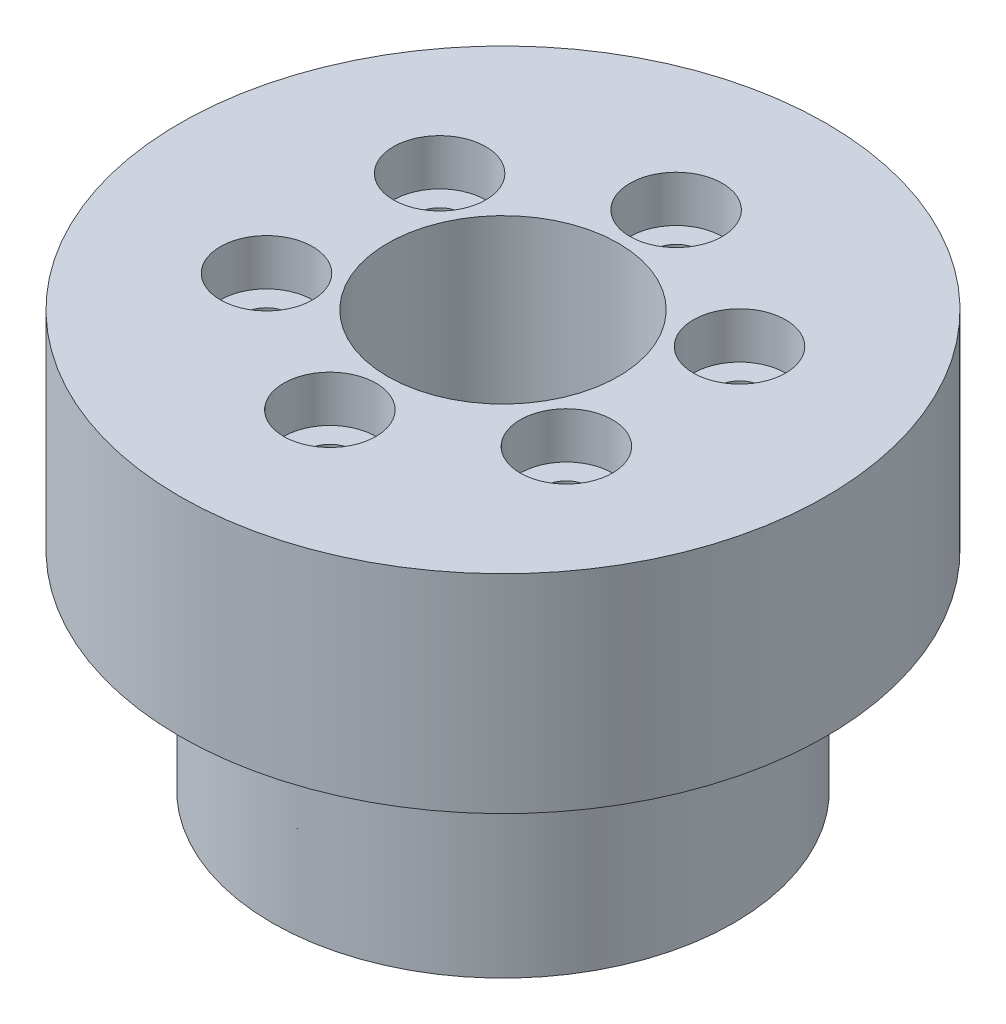
SolidWorks part; units mm, degrees
material "1060 Alloy"
ref_plane "Front" through (0, 0, 0) normal (0, 0, 1) x (1, 0, 0)
ref_plane "Top" through (0, 0, 0) normal (0, 1, 0) x (1, 0, 0)
ref_plane "Right" through (0, 0, 0) normal (1, 0, 0) x (0, 0, -1)
sketch "Sketch1" plane through (0, 0, 0) normal (0, 0, 1) x (1, 0, 0)
  line L0 (0, 0) -> (20, 0)
  line L1 (20, 0) -> (20, 18)
  line L2 (20, 18) -> (28, 18)
  line L3 (28, 18) -> (28, 36)
  line L6 (28, 36) -> (0, 36)
  line L7 (0, 36) -> (0, 0)
  point P3 (20, 38)
  point P8 (20, 38)
  point P11 (24.6535, 38)
  dimension "D1" = 18
  dimension "D2" = 18
  dimension "D3" = 8
  dimension "D4" = 20
revolve "Revolve1" add sketch "Sketch1" angle 360 about L7
sketch "Sketch2" plane through (0, 36, 0) normal (0, 1, 0) x (1, 0, 0)
  line L0 (0, 0) -> (0, 15) construction
  circle A0 centre (0, 0) radius 15 construction
  circle A1 centre (0, 15) radius 2
  circle A2 centre (0, 0) radius 15 construction
  circle A3 centre (12.9904, 7.5) radius 2
  circle A4 centre (0, 0) radius 15 construction
  circle A5 centre (12.9904, -7.5) radius 2
  circle A6 centre (0, 0) radius 15 construction
  circle A7 centre (0, -15) radius 2
  circle A8 centre (0, 0) radius 15 construction
  circle A9 centre (-12.9904, -7.5) radius 2
  circle A10 centre (0, 0) radius 15 construction
  circle A11 centre (-12.9904, 7.5) radius 2
  point P23 (0, 0)
  dimension "D1" = 30
  dimension "D2" = 4
extrude "Cut-Extrude1" cut sketch "Sketch2" against normal through all
sketch "Sketch3" plane through (0, 36, 0) normal (0, 1, 0) x (1, 0, 0)
  line L0 (0, 13) -> (0, 10) construction
  circle A0 centre (0, 0) radius 10
  circle A1 centre (0, 15) radius 2 construction
  dimension "D1" = 3
extrude "Cut-Extrude2" cut sketch "Sketch3" against normal through all
sketch "Sketch4" plane through (0, 36, 0) normal (0, 1, 0) x (1, 0, 0)
  circle A0 centre (0, 15) radius 4
  circle A1 centre (12.9904, 7.5) radius 4
  circle A2 centre (12.9904, -7.5) radius 4
  circle A3 centre (0, -15) radius 4
  circle A4 centre (-12.9904, -7.5) radius 4
  circle A5 centre (-12.9904, 7.5) radius 4
  point P15 (0, 0)
extrude "Cut-Extrude3" cut sketch "Sketch4" against normal blind 4
equation "\"D1@base\" = \"motor mount plate thickness\""
equation "\"coupler motor shaft hole ID\"= 8mm"
equation "\"coupler OD\"= 17mm"
equation "\"coupler length\"= 25mm"
equation "\"square plate bolt pattern diameter\"= 3.5in"
equation "\"motor mount m4 screw hole diameter\"= 4mm"
equation "\"motor mount m4 head diameter\"= 7.25mm"
equation "\"motor mount m4 head depth\"= 4mm"
equation "\"motor mount plate thickness\"= 8mm + \"motor mount m4 head depth\""
equation "\"motor shaft pride\"= 32mm"
equation "\"motor mount m4 pattern diamater\" = 30mm"
equation "\"motor OD\" = 64mm"
equation "\"square plate bolt bore\" = \"m8 clearance\""
equation "\"square plate bolt head diameter\" = 13.5mm"
equation "\"motor to bearing plate distance\" = \"motor shaft pride\" + 2mm +\"coupler length\"/2"
equation "\"motor mount center bore\"= \"coupler OD\"+ 4mm"
equation "\"motor mount post radius\"= ( 3 * \"square plate bolt bore\" ) / 2"
equation "\"motor shaft diameter\"= 8mm"
equation "\"D1\" = 20mm"
equation "\"z\" = 8\t\t\t\t'number of blades"
equation "\"de\" = 0.43in\t\t\t'entrance eye diameter"
equation "\"de_length\" = 4mm\t\t'entrance eye consistent length"
equation "\"d_exit\" = 0.18in \t\t'throat aka d1"
equation "\"d2\" = 2.1in \t\t\t'outer diameter of the impeller"
equation "\"b2\" = .2in\t\t\t'tip height from disc surface at d2; slightly higher than d_exit"
equation "\"theta\" = 12\t\t\t'angle of blades from inner to outer "
equation "\"ae\" = 3.14*(\"de\"^2)/4\t\t'entrance eye area'"
equation "\"ce\" = 3.14*\"de\"\t\t'entrance eye circumference"
equation "\"av_ratio\" = .325\t\t'ratio of av/ae at N_s of 470, range is .275 to .375, .325 ideal. High ratio means bigger area means smaller blades"
equation "\"av\" = \"ae\"*\"av_ratio\"\t\t'area between just two blades"
equation "\"min blade thickness\" = .15in"
equation "\"diffuser cartridge OD\" =.75in"
equation "\"diffuser flange bolt pattern diameter\" = 1.4in"
equation "\"bearing OD\" = 30mm"
equation "\"bearing ID\"= 10mm"
equation "\"bearing depth\"= 9mm"
equation "\"bearing outer race thickness\"= 1mm"
equation "\"bearing inner race thickness\"= 1mm"
equation "\"bearing bore\" = \"bearing depth\" + 1mm"
equation "\"lower seal OD\" = .917in\t\t'this is https://www.mcmaster.com/#9281k121/=174001b"
equation "\"lower seal ID\"= .375in"
equation "\"lower seal depth\" = .625in + .218in"
equation "\"lower seal bore\" = \"lower seal depth\" + 1mm"
equation "\"upper seal OD\" = 1.125in\t'this is https://www.mcmaster.com/#5154t33/=173zuau, needs to be visually inspected before machining!"
equation "\"upper seal ID\"= 0.625in"
equation "\"upper seal depth\"= .25in\t'aka height; these values need to be confirmed by inspection!! We may want to compress the height."
equation "\"upper seal bore\" = \"upper seal depth\" + 1mm"
equation "\"big o-ring thickness\" = .139in"
equation "\"big o-ring OD\" = 2.734in"
equation "\"big o-ring ID\" = 3.012in"
equation "\"big o-ring groove depth\" = \"big o-ring thickness\"*4/5"
equation "\"impeller upper clearance\"= .5mm"
equation "\"impeller horizontal clearance\"= (\"d2\"*1.15 - \"d2\")/2 \t\t'clearance based on D2-D3 ratio for circular volute, ranges 1.15 to 1.2"
equation "\"impeller bottom clearance\"= .5mm"
equation "\"impeller base thickness\"= 2mm"
equation "\"impeller dowel diameter\" = 2mm"
equation "\"impeller bolt head depth\" = 4mm"
equation "\"impeller bolt stop depth\" = 3mm"
equation "\"impeller shaft bore depth\" = 12mm"
equation "\"impeller shaft bore\" = 8mm"
equation "\"impeller boss depth\" = \"impeller shaft bore depth\"+\"impeller bolt stop depth\"+\"impeller bolt head depth\"-\"impeller base thickness\""
equation "\"impeller boss diameter\" = \"upper seal ID\""
equation "\"impeller dowel length\" = 2mm*2 + \"impeller shaft bore\""
equation "\"square plate bolt head depth\" = 8mm"
equation "\"bearing plate stop ID\" = \"bearing OD\" - 4mm"
equation "\"bearing plate stop depth\" = 3mm"
equation "\"lower seal plate lip depth\" = 2mm"
equation "\"lower seal plate lip ID\" = \"lower seal OD\" - 3mm"
equation "\"lower seal plate thickness\" = \"lower seal plate lip depth\" + \"lower seal bore\""
equation "\"shaft coupler section diameter\" = 8mm"
equation "\"shaft coupler section length\" = \"motor to bearing plate distance\" - \"motor shaft pride\" - 2mm"
equation "\"shaft bearing section diameter\" = \"bearing ID\""
equation "\"shaft bearing section length\" = \"bearing plate stop depth\" + \"bearing depth\""
equation "\"shaft bearing stop diameter\" = \"bearing ID\" + 4mm"
equation "\"shaft bearing stop length\" = 3mm"
equation "\"shaft lower seal section diameter\" = \"lower seal ID\""
equation "\"shaft lower seal section length\" = \"lower seal plate thickness\" + 1mm"
equation "\"shaft impeller section diameter\" = \"impeller shaft bore\""
equation "\"upper seal plate lip ID\" = \"upper seal OD\" - 3mm"
equation "\"upper seal plate riser\" = 6.59mm \t\t'this number needs to be read from the housing file"
equation "\"upper seal plate pressure hole diameter\" = .125in\t'this is 1/8 drill "
equation "\"upper seal plate pressure tap diameter\" = .328125in \t'this is 21/64 drill for a 1/8 ANPT tap"
equation "\"upper seal plate pressure tap grip\" = 5mm\t\t'this is the area around the tap so it doesn't crack"
equation "\"upper seal plate pressure tap depth\" = 12mm"
equation "\"impeller cavity diameter\"= 2 * \"impeller horizontal clearance\" + \"d2\" \t\t\t\t\t\t\t\t\t'called D3 analytically"
equation "\"impeller cavity outer height\"= \"impeller bottom clearance\" + \"impeller upper clearance\" + \"impeller base thickness\" + \"b2\" \t\t'this is height at impeller diameter d2, not at d3"
equation "\"impeller housing diameter\" = 4.5in"
equation "\"impeller housing bolt count\" = 8"
equation "\"impeller housing bolt pattern diameter\" = 3.5in"
equation "\"impeller housing threaded inlet diameter\" = 0.71875in \t'this is the 23/32 drill size for 1/2 NPT fitting https://www.mcmaster.com/#50715k269/=176pljy"
equation "\"impeller housing threaded inlet depth\"= .6in"
equation "\"impeller housing exit threaded diameter\"= 0.515625in \t\t'this is the 33/64 drill size for 9/16-18 fitting, expecting swagelok SS-8FK0-1-6STH fitting"
equation "\"impeller housing exit threaded depth\"= 10mm"
equation "\"impeller housing diffuser conical angle\"=10"
equation "\"impeller housing diffuser tangent angle\"=5"
equation "\"impeller housing diffuser final diameter\" = .38in\t\t'aka d2'"
equation "\"impeller housing outlet grip\" = 5mm"
equation "\"end mill size\" = 0.375in\t'for 3/8 endmill"
equation "\"m4 clearance\" = 0.171875in \t'this is 11/64 bit for 4.36mm"
equation "\"m4 tap\" = 0.125in\t\t'this is 1/8 bit for 3.17mm"
equation "\"m4 head bore diameter\" = 7.5mm"
equation "\"m4 head bore depth\" = 5mm\t'actual is ~4mm"
equation "\"m6 clearance\" = 0.234375in\t'this is 15/64 bit = 5.95mm, could use 6mm bit, B bit for 6.04mm or 1/4 bit for 6.35mm"
equation "\"m6 tap\" = 5mm\t\t\t'5mm is appropriate, could use 13/64 or #5,6,7"
equation "\"m6 head bore diameter\" = 11mm\t\t"
equation "\"m6 head bore depth\" = 7mm\t'actual is 6mm"
equation "\"m8 clearance\" = 0.3125in\t'this is 5/16in for 7.93mm, could use 8mm, O,P, or 21/64"
equation "\"m8 tap\" = 0.265625in\t\t'this is 17/64 for 6.746875mm"
equation "\"m8 head bore diameter\" = 14mm"
equation "\"m8 head bore depth\" = 9mm\t'actual is 8mm"
